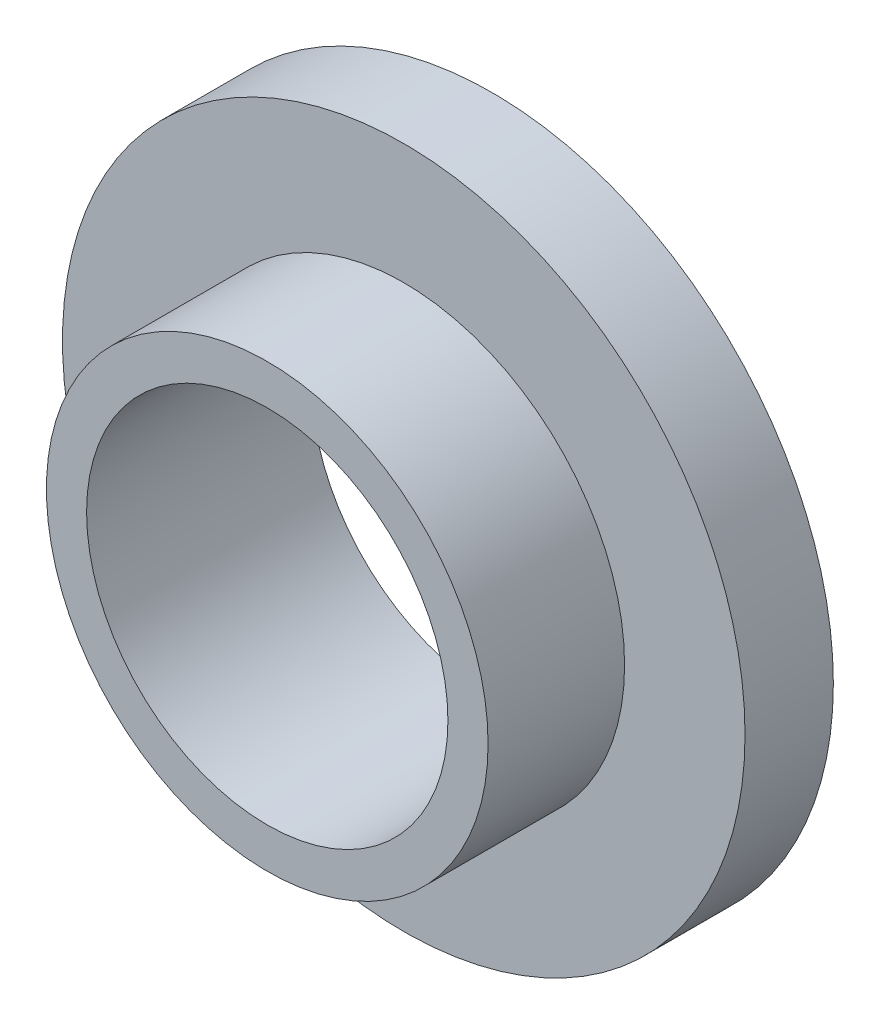
SolidWorks part; units mm, degrees
ref_plane "Front Plane" through (0, 0, 0) normal (0, 0, 1) x (1, 0, 0)
ref_plane "Top Plane" through (0, 0, 0) normal (0, 1, 0) x (1, 0, 0)
ref_plane "Right Plane" through (0, 0, 0) normal (1, 0, 0) x (0, 0, -1)
sketch "Sketch1" plane through (0, 0, 0) normal (0, 0, 1) x (1, 0, 0)
  circle A0 centre (0, 0) radius 2.25
  circle A1 centre (0, 0) radius 4.25
  dimension "D1" = 4.5
  dimension "D2" = 2
extrude "Boss-Extrude1" add sketch "Sketch1" along normal blind 1.1
sketch "Sketch2" plane through (0, 0, 1.1) normal (0, 0, 1) x (1, 0, 0)
  circle A0 centre (0, 0) radius 2.75
  circle A1 centre (0, 0) radius 2.25 construction
  circle A2 centre (0, 0) radius 2.25
  dimension "D1" = 0.5
extrude "Boss-Extrude2" add sketch "Sketch2" along normal blind 1.7
